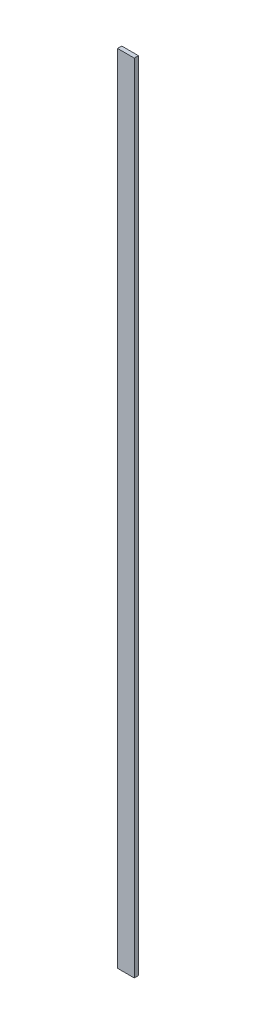
SolidWorks part; units mm, degrees
material "Spruce"
ref_plane "Front Plane" through (0, 0, 0) normal (0, 0, 1) x (1, 0, 0)
ref_plane "Top Plane" through (0, 0, 0) normal (0, 1, 0) x (1, 0, 0)
ref_plane "Right Plane" through (0, 0, 0) normal (1, 0, 0) x (0, 0, -1)
sketch "Sketch1" plane through (0, 0, 0) normal (0, 0, 1) x (1, 0, 0)
  line L0 (-34.5198, -88.3502) -> (-28.1698, -88.3502)
  line L4 (-34.5198, -88.3502) -> (-34.5198, 213.9142)
  line L5 (-34.5198, 213.9142) -> (-28.1698, 213.9142)
  line L6 (-28.1698, 213.9142) -> (-28.1698, -88.3502)
extrude "Boss-Extrude2" add sketch "Sketch1" along normal blind 1.5875
